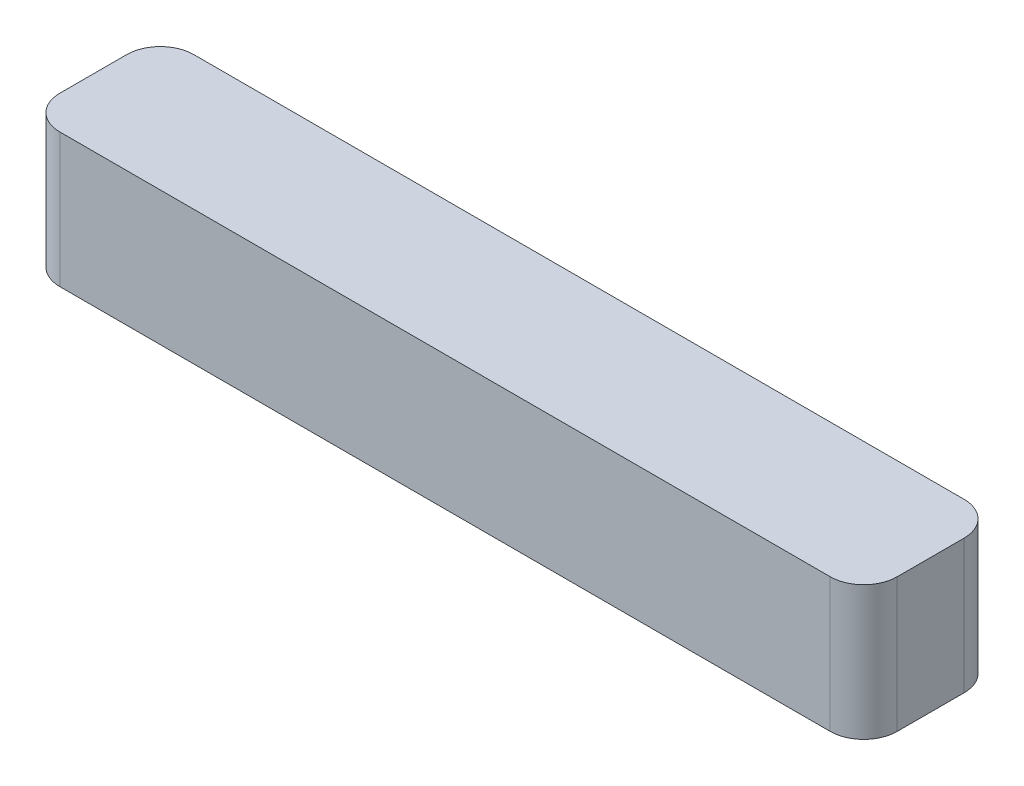
SolidWorks part; units mm, degrees
ref_plane "前视基准面" through (0, 0, 0) normal (0, 0, 1) x (1, 0, 0)
ref_plane "上视基准面" through (0, 0, 0) normal (0, 1, 0) x (1, 0, 0)
ref_plane "右视基准面" through (0, 0, 0) normal (1, 0, 0) x (0, 0, -1)
sketch "Sketch1" plane through (0, 0, 0) normal (0, 1, 0) x (1, 0, 0)
  line L1 (-11.5, 2) -> (11.5, 2)
  line L2 (-12.5, 1) -> (-12.5, -1)
  line L3 (-11.5, -2) -> (11.5, -2)
  line L4 (12.5, 1) -> (12.5, -1)
  line L5 (-12.5, 2) -> (12.5, -2) construction
  line L6 (-12.5, -2) -> (12.5, 2) construction
  arc A0 (11.5, 2) -> (12.5, 1) centre (11.5, 1) cw
  arc A1 (11.5, -2) -> (12.5, -1) centre (11.5, -1) ccw
  arc A2 (-12.5, -1) -> (-11.5, -2) centre (-11.5, -1) ccw
  arc A3 (-11.5, 2) -> (-12.5, 1) centre (-11.5, 1) ccw
  point P0 (0, 0)
  dimension "D3" = 1
  dimension "D1" = 25
  dimension "D2" = 4
extrude "Boss-Extrude1" add sketch "Sketch1" along normal blind 4
